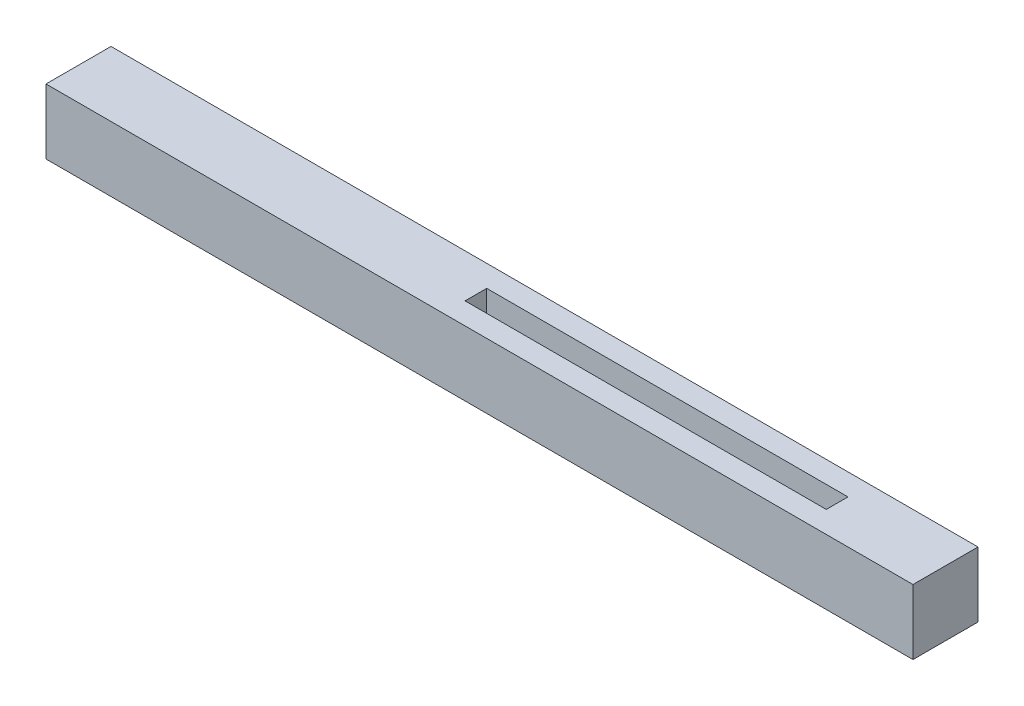
SolidWorks part; units mm, degrees
ref_plane "前视基准面" through (0, 0, 0) normal (0, 0, 1) x (1, 0, 0)
ref_plane "上视基准面" through (0, 0, 0) normal (0, 1, 0) x (1, 0, 0)
ref_plane "右视基准面" through (0, 0, 0) normal (1, 0, 0) x (0, 0, -1)
sketch "草图1" plane through (0, 0, 0) normal (0, 1, 0) x (1, 0, 0)
  line L1 (-60.2409, 18.3626) -> (59.7591, 18.3626)
  line L2 (-60.2409, 18.3626) -> (-60.2409, 9.3626)
  line L3 (-60.2409, 9.3626) -> (59.7591, 9.3626)
  line L4 (59.7591, 18.3626) -> (59.7591, 9.3626)
  line L5 (-5.2409, 15.3626) -> (44.7591, 15.3626)
  line L6 (-5.2409, 15.3626) -> (-5.2409, 12.3626)
  line L7 (-5.2409, 12.3626) -> (44.7591, 12.3626)
  line L8 (44.7591, 15.3626) -> (44.7591, 12.3626)
  point P8 (59.7591, 13.8626)
  dimension "D1" = 9
  dimension "D2" = 120
  dimension "D3" = 3
  dimension "D4" = 50
  dimension "D5" = 3
  dimension "D6" = 15
extrude "凸台-拉伸1" add sketch "草图1" along normal blind 9
